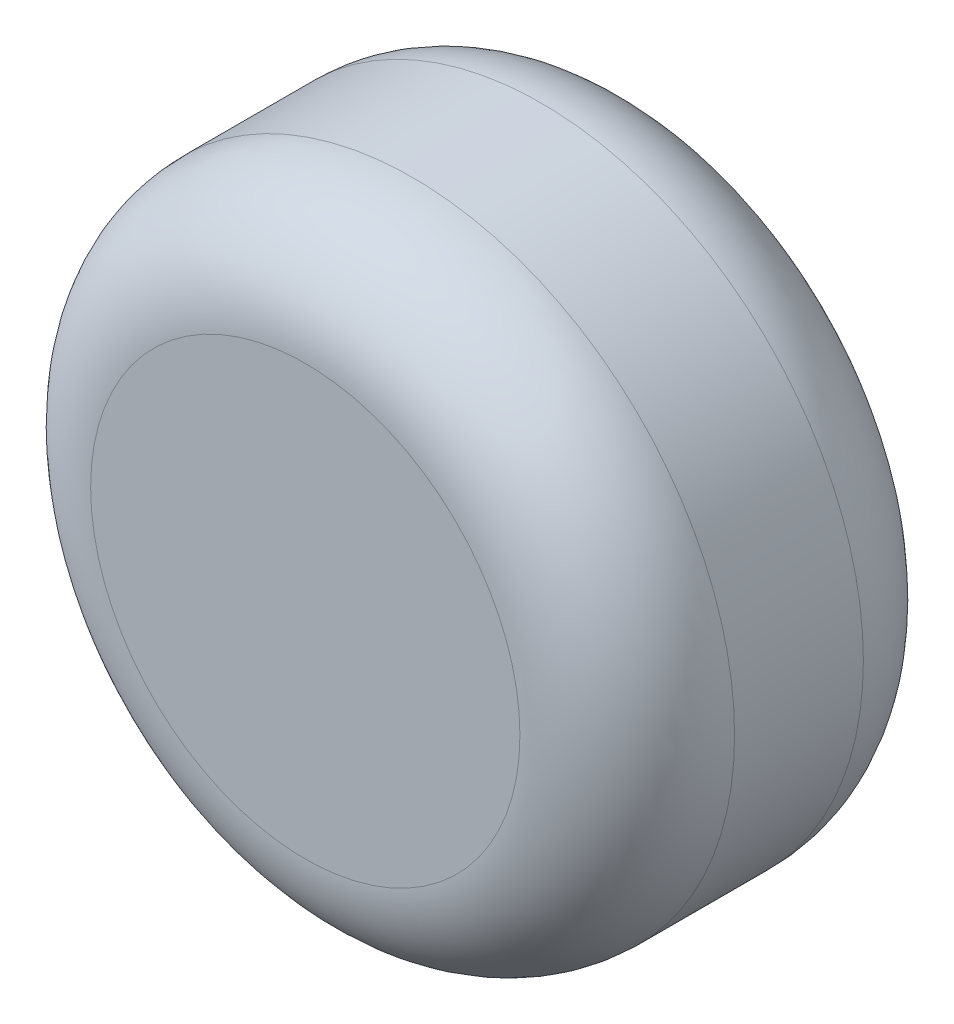
SolidWorks part; units mm, degrees
ref_plane "Спереди" through (0, 0, 0) normal (0, 0, 1) x (1, 0, 0)
ref_plane "Сверху" through (0, 0, 0) normal (0, 1, 0) x (1, 0, 0)
ref_plane "Справа" through (0, 0, 0) normal (1, 0, 0) x (0, 0, -1)
sketch "Эскиз1" plane through (0, 0, 0) normal (0, 0, 1) x (1, 0, 0)
  circle A0 centre (0, 0) radius 30
  dimension "D1" = 60
extrude "Бобышка-Вытянуть1" add sketch "Эскиз1" along normal blind 32
fillet "Скругление1" radius 10 2 edges at (30, 0, 0) (30, 0, 32)
sketch "Эскиз2" plane through (0, 0, 0) normal (0, 0, -1) x (-1, 0, 0)
  line L0 (-1.199, 2.75) -> (1.199, 2.75)
  line L7 (-1.199, -2.75) -> (1.199, -2.75)
  circle A0 centre (0, 0) radius 5
  arc A1 (-1.199, 2.75) -> (-1.199, -2.75) centre (0, 0) ccw
  arc A4 (1.199, -2.75) -> (1.199, 2.75) centre (0, 0) ccw
  point P9 (0, 0)
  dimension "D1" = 10
  dimension "D2" = 6
  dimension "D4" = 2.3979
  dimension "D5" = 2.3979
extrude "Бобышка-Вытянуть2" add sketch "Эскиз2" along normal blind 12
